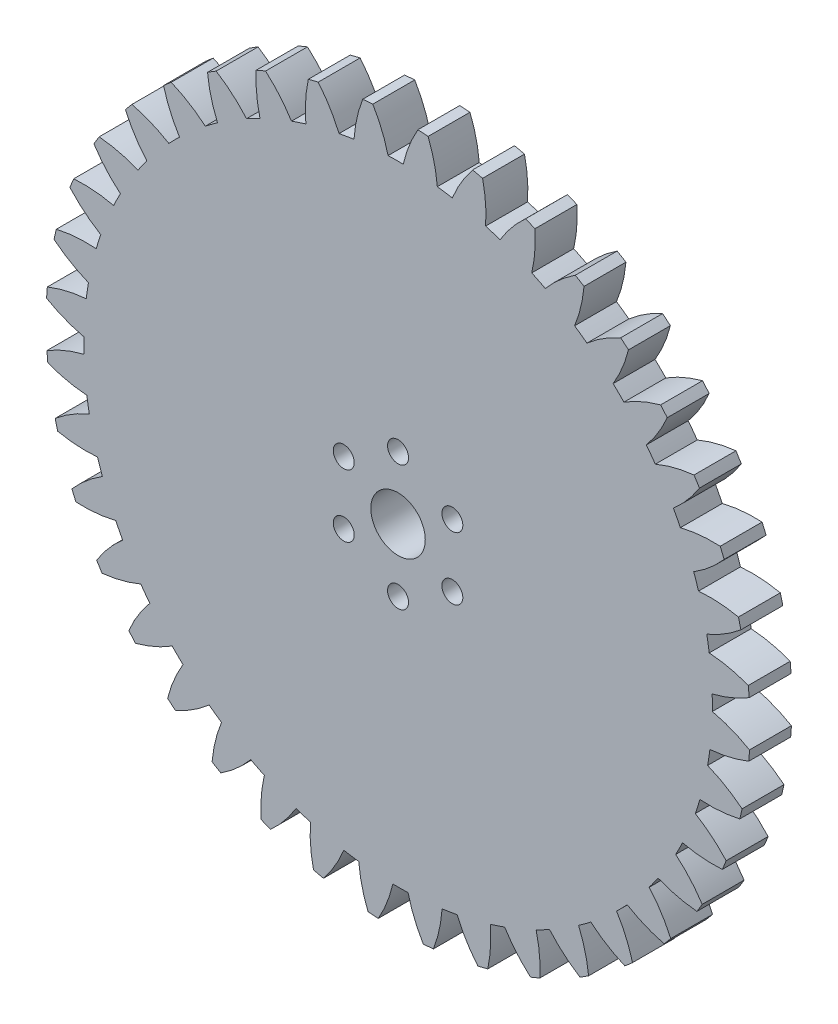
SolidWorks part; units mm, degrees
ref_plane "Front Plane" through (0, 0, 0) normal (0, 0, 1) x (1, 0, 0)
ref_plane "Top Plane" through (0, 0, 0) normal (0, 1, 0) x (1, 0, 0)
ref_plane "Right Plane" through (0, 0, 0) normal (1, 0, 0) x (0, 0, -1)
sketch "Sketch1" plane through (0, 0, 0) normal (0, 0, 1) x (1, 0, 0)
  circle A0 centre (0, 0) radius 9.5 construction
  circle A1 centre (0, 9.5) radius 1.5875
  circle A2 centre (8.2272, 4.75) radius 1.5875
  circle A3 centre (8.2272, -4.75) radius 1.5875
  circle A4 centre (0, -9.5) radius 1.5875
  circle A5 centre (-8.2272, -4.75) radius 1.5875
  circle A6 centre (-8.2272, 4.75) radius 1.5875
  circle A7 centre (0, 0) radius 4.125
  point P17 (0, 0)
  arc B0 (-53.2553, 3.0046) -> (-47.6173, 0.7826) centre (-43.069, 20.587) ccw
  arc B1 (-47.6173, 0.7826) -> (-47.5997, -1.5139) centre (0, 0) ccw
  arc B2 (-47.5997, -1.5139) -> (-53.2029, -3.8222) centre (-42.7477, -21.2461) ccw
  arc B3 (-53.2029, -3.8222) -> (-53.0697, -5.3634) centre (0, 0) ccw
  arc B4 (-53.0697, -5.3634) -> (-47.1535, -6.676) centre (-45.7593, 13.5961) ccw
  arc B5 (-47.1535, -6.676) -> (-46.7768, -8.9415) centre (0, 0) ccw
  arc B6 (-46.7768, -8.9415) -> (-51.9499, -12.0979) centre (-38.8978, -27.6718) ccw
  arc B7 (-51.9499, -12.0979) -> (-51.5773, -13.5993) centre (0, 0) ccw
  arc B8 (-51.5773, -13.5993) -> (-45.5286, -13.9703) centre (-47.3228, 6.2704) ccw
  arc B9 (-45.5286, -13.9703) -> (-44.8022, -16.1489) centre (0, 0) ccw
  arc B10 (-44.8022, -16.1489) -> (-49.4178, -20.0758) centre (-34.0901, -33.416) ccw
  arc B11 (-49.4178, -20.0758) -> (-48.8149, -21.5003) centre (0, 0) ccw
  arc B12 (-48.8149, -21.5003) -> (-42.7826, -20.9205) centre (-47.7211, -1.2098) ccw
  arc B13 (-42.7826, -20.9205) -> (-41.7243, -22.9587) centre (0, 0) ccw
  arc B14 (-41.7243, -22.9587) -> (-45.6688, -27.5592) centre (-28.4429, -38.3375) ccw
  arc B15 (-45.6688, -27.5592) -> (-44.8505, -28.8719) centre (0, 0) ccw
  arc B16 (-44.8505, -28.8719) -> (-38.9832, -27.3556) centre (-46.9443, -8.6601) ccw
  arc B17 (-38.9832, -27.3556) -> (-37.6191, -29.2031) centre (0, 0) ccw
  arc B18 (-37.6191, -29.2031) -> (-40.7954, -34.3641) centre (-22.0955, -42.3149) ccw
  arc B19 (-40.7954, -34.3641) -> (-39.7818, -35.5326) centre (0, 0) ccw
  arc B20 (-39.7818, -35.5326) -> (-34.2239, -33.1172) centre (-45.0116, -15.8972) ccw
  arc B21 (-34.2239, -33.1172) -> (-32.5876, -34.7285) centre (0, 0) ccw
  arc B22 (-32.5876, -34.7285) -> (-34.9174, -40.3228) centre (-15.2039, -45.2505) ccw
  arc B23 (-34.9174, -40.3228) -> (-33.7334, -41.3184) centre (0, 0) ccw
  arc B24 (-33.7334, -41.3184) -> (-28.6219, -38.0632) centre (-41.9706, -22.7428) ccw
  arc B25 (-28.6219, -38.0632) -> (-26.7536, -39.3988) centre (0, 0) ccw
  arc B26 (-26.7536, -39.3988) -> (-28.1796, -45.2887) centre (-7.938, -47.0718) ccw
  arc B27 (-28.1796, -45.2887) -> (-26.8545, -46.0868) centre (0, 0) ccw
  arc B28 (-26.8545, -46.0868) -> (-22.3151, -42.072) centre (-37.8961, -29.0284) ccw
  arc B29 (-22.3151, -42.072) -> (-20.2609, -43.0989) centre (0, 0) ccw
  arc B30 (-20.2609, -43.0989) -> (-20.748, -49.1394) centre (-0.4766, -47.734) ccw
  arc B31 (-20.748, -49.1394) -> (-19.3143, -49.7203) centre (0, 0) ccw
  arc B32 (-19.3143, -49.7203) -> (-15.4588, -45.0449) centre (-32.8885, -34.5993) ccw
  arc B33 (-15.4588, -45.0449) -> (-13.2693, -45.7378) centre (0, 0) ccw
  arc B34 (-13.2693, -45.7378) -> (-12.8054, -51.7801) centre (6.9965, -47.2209) ccw
  arc B35 (-12.8054, -51.7801) -> (-11.2986, -52.1296) centre (0, 0) ccw
  arc B36 (-11.2986, -52.1296) -> (-8.2219, -46.9086) centre (-27.071, -39.3182) ccw
  arc B37 (-8.2219, -46.9086) -> (-5.951, -47.2505) centre (0, 0) ccw
  arc B38 (-5.951, -47.2505) -> (-4.5476, -53.1458) centre (14.2973, -45.545) ccw
  arc B39 (-4.5476, -53.1458) -> (-3.0046, -53.2553) centre (0, 0) ccw
  arc B40 (-3.0046, -53.2553) -> (-0.7826, -47.6173) centre (-20.587, -43.069) ccw
  arc B41 (-0.7826, -47.6173) -> (1.5139, -47.5997) centre (0, 0) ccw
  arc B42 (1.5139, -47.5997) -> (3.8222, -53.2029) centre (21.2461, -42.7477) ccw
  arc B43 (3.8222, -53.2029) -> (5.3634, -53.0697) centre (0, 0) ccw
  arc B44 (5.3634, -53.0697) -> (6.676, -47.1535) centre (-13.5961, -45.7593) ccw
  arc B45 (6.676, -47.1535) -> (8.9415, -46.7768) centre (0, 0) ccw
  arc B46 (8.9415, -46.7768) -> (12.0979, -51.9499) centre (27.6718, -38.8978) ccw
  arc B47 (12.0979, -51.9499) -> (13.5993, -51.5773) centre (0, 0) ccw
  arc B48 (13.5993, -51.5773) -> (13.9703, -45.5286) centre (-6.2704, -47.3228) ccw
  arc B49 (13.9703, -45.5286) -> (16.1489, -44.8022) centre (0, 0) ccw
  arc B50 (16.1489, -44.8022) -> (20.0758, -49.4178) centre (33.416, -34.0901) ccw
  arc B51 (20.0758, -49.4178) -> (21.5003, -48.8149) centre (0, 0) ccw
  arc B52 (21.5003, -48.8149) -> (20.9205, -42.7826) centre (1.2098, -47.7211) ccw
  arc B53 (20.9205, -42.7826) -> (22.9587, -41.7243) centre (0, 0) ccw
  arc B54 (22.9587, -41.7243) -> (27.5592, -45.6688) centre (38.3375, -28.4429) ccw
  arc B55 (27.5592, -45.6688) -> (28.8719, -44.8505) centre (0, 0) ccw
  arc B56 (28.8719, -44.8505) -> (27.3556, -38.9832) centre (8.6601, -46.9443) ccw
  arc B57 (27.3556, -38.9832) -> (29.2031, -37.6191) centre (0, 0) ccw
  arc B58 (29.2031, -37.6191) -> (34.3641, -40.7954) centre (42.3149, -22.0955) ccw
  arc B59 (34.3641, -40.7954) -> (35.5326, -39.7818) centre (0, 0) ccw
  arc B60 (35.5326, -39.7818) -> (33.1172, -34.2239) centre (15.8972, -45.0116) ccw
  arc B61 (33.1172, -34.2239) -> (34.7285, -32.5876) centre (0, 0) ccw
  arc B62 (34.7285, -32.5876) -> (40.3228, -34.9174) centre (45.2505, -15.2039) ccw
  arc B63 (40.3228, -34.9174) -> (41.3184, -33.7334) centre (0, 0) ccw
  arc B64 (41.3184, -33.7334) -> (38.0632, -28.6219) centre (22.7428, -41.9706) ccw
  arc B65 (38.0632, -28.6219) -> (39.3988, -26.7536) centre (0, 0) ccw
  arc B66 (39.3988, -26.7536) -> (45.2887, -28.1796) centre (47.0718, -7.938) ccw
  arc B67 (45.2887, -28.1796) -> (46.0868, -26.8545) centre (0, 0) ccw
  arc B68 (46.0868, -26.8545) -> (42.072, -22.3151) centre (29.0284, -37.8961) ccw
  arc B69 (42.072, -22.3151) -> (43.0989, -20.2609) centre (0, 0) ccw
  arc B70 (43.0989, -20.2609) -> (49.1394, -20.748) centre (47.734, -0.4766) ccw
  arc B71 (49.1394, -20.748) -> (49.7203, -19.3143) centre (0, 0) ccw
  arc B72 (49.7203, -19.3143) -> (45.0449, -15.4588) centre (34.5993, -32.8885) ccw
  arc B73 (45.0449, -15.4588) -> (45.7378, -13.2693) centre (0, 0) ccw
  arc B74 (45.7378, -13.2693) -> (51.7801, -12.8054) centre (47.2209, 6.9965) ccw
  arc B75 (51.7801, -12.8054) -> (52.1296, -11.2986) centre (0, 0) ccw
  arc B76 (52.1296, -11.2986) -> (46.9086, -8.2219) centre (39.3182, -27.071) ccw
  arc B77 (46.9086, -8.2219) -> (47.2505, -5.951) centre (0, 0) ccw
  arc B78 (47.2505, -5.951) -> (53.1458, -4.5476) centre (45.545, 14.2973) ccw
  arc B79 (53.1458, -4.5476) -> (53.2553, -3.0046) centre (0, 0) ccw
  arc B80 (53.2553, -3.0046) -> (47.6173, -0.7826) centre (43.069, -20.587) ccw
  arc B81 (47.6173, -0.7826) -> (47.5997, 1.5139) centre (0, 0) ccw
  arc B82 (47.5997, 1.5139) -> (53.2029, 3.8222) centre (42.7477, 21.2461) ccw
  arc B83 (53.2029, 3.8222) -> (53.0697, 5.3634) centre (0, 0) ccw
  arc B84 (53.0697, 5.3634) -> (47.1535, 6.676) centre (45.7593, -13.5961) ccw
  arc B85 (47.1535, 6.676) -> (46.7768, 8.9415) centre (0, 0) ccw
  arc B86 (46.7768, 8.9415) -> (51.9499, 12.0979) centre (38.8978, 27.6718) ccw
  arc B87 (51.9499, 12.0979) -> (51.5773, 13.5993) centre (0, 0) ccw
  arc B88 (51.5773, 13.5993) -> (45.5286, 13.9703) centre (47.3228, -6.2704) ccw
  arc B89 (45.5286, 13.9703) -> (44.8022, 16.1489) centre (0, 0) ccw
  arc B90 (44.8022, 16.1489) -> (49.4178, 20.0758) centre (34.0901, 33.416) ccw
  arc B91 (49.4178, 20.0758) -> (48.8149, 21.5003) centre (0, 0) ccw
  arc B92 (48.8149, 21.5003) -> (42.7826, 20.9205) centre (47.7211, 1.2098) ccw
  arc B93 (42.7826, 20.9205) -> (41.7243, 22.9587) centre (0, 0) ccw
  arc B94 (41.7243, 22.9587) -> (45.6688, 27.5592) centre (28.4429, 38.3375) ccw
  arc B95 (45.6688, 27.5592) -> (44.8505, 28.8719) centre (0, 0) ccw
  arc B96 (44.8505, 28.8719) -> (38.9832, 27.3556) centre (46.9443, 8.6601) ccw
  arc B97 (38.9832, 27.3556) -> (37.6191, 29.2031) centre (0, 0) ccw
  arc B98 (37.6191, 29.2031) -> (40.7954, 34.3641) centre (22.0955, 42.3149) ccw
  arc B99 (40.7954, 34.3641) -> (39.7818, 35.5326) centre (0, 0) ccw
  arc B100 (39.7818, 35.5326) -> (34.2239, 33.1172) centre (45.0116, 15.8972) ccw
  arc B101 (34.2239, 33.1172) -> (32.5876, 34.7285) centre (0, 0) ccw
  arc B102 (32.5876, 34.7285) -> (34.9174, 40.3228) centre (15.2039, 45.2505) ccw
  arc B103 (34.9174, 40.3228) -> (33.7334, 41.3184) centre (0, 0) ccw
  arc B104 (33.7334, 41.3184) -> (28.6219, 38.0632) centre (41.9706, 22.7428) ccw
  arc B105 (28.6219, 38.0632) -> (26.7536, 39.3988) centre (0, 0) ccw
  arc B106 (26.7536, 39.3988) -> (28.1796, 45.2887) centre (7.938, 47.0718) ccw
  arc B107 (28.1796, 45.2887) -> (26.8545, 46.0868) centre (0, 0) ccw
  arc B108 (26.8545, 46.0868) -> (22.3151, 42.072) centre (37.8961, 29.0284) ccw
  arc B109 (22.3151, 42.072) -> (20.2609, 43.0989) centre (0, 0) ccw
  arc B110 (20.2609, 43.0989) -> (20.748, 49.1394) centre (0.4766, 47.734) ccw
  arc B111 (20.748, 49.1394) -> (19.3143, 49.7203) centre (0, 0) ccw
  arc B112 (19.3143, 49.7203) -> (15.4588, 45.0449) centre (32.8885, 34.5993) ccw
  arc B113 (15.4588, 45.0449) -> (13.2693, 45.7378) centre (0, 0) ccw
  arc B114 (13.2693, 45.7378) -> (12.8054, 51.7801) centre (-6.9965, 47.2209) ccw
  arc B115 (12.8054, 51.7801) -> (11.2986, 52.1296) centre (0, 0) ccw
  arc B116 (11.2986, 52.1296) -> (8.2219, 46.9086) centre (27.071, 39.3182) ccw
  arc B117 (8.2219, 46.9086) -> (5.951, 47.2505) centre (0, 0) ccw
  arc B118 (5.951, 47.2505) -> (4.5476, 53.1458) centre (-14.2973, 45.545) ccw
  arc B119 (4.5476, 53.1458) -> (3.0046, 53.2553) centre (0, 0) ccw
  arc B120 (3.0046, 53.2553) -> (0.7826, 47.6173) centre (20.587, 43.069) ccw
  arc B121 (0.7826, 47.6173) -> (-1.5139, 47.5997) centre (0, 0) ccw
  arc B122 (-1.5139, 47.5997) -> (-3.8222, 53.2029) centre (-21.2461, 42.7477) ccw
  arc B123 (-3.8222, 53.2029) -> (-5.3634, 53.0697) centre (0, 0) ccw
  arc B124 (-5.3634, 53.0697) -> (-6.676, 47.1535) centre (13.5961, 45.7593) ccw
  arc B125 (-6.676, 47.1535) -> (-8.9415, 46.7768) centre (0, 0) ccw
  arc B126 (-8.9415, 46.7768) -> (-12.0979, 51.9499) centre (-27.6718, 38.8978) ccw
  arc B127 (-12.0979, 51.9499) -> (-13.5993, 51.5773) centre (0, 0) ccw
  arc B128 (-13.5993, 51.5773) -> (-13.9703, 45.5286) centre (6.2704, 47.3228) ccw
  arc B129 (-13.9703, 45.5286) -> (-16.1489, 44.8022) centre (0, 0) ccw
  arc B130 (-16.1489, 44.8022) -> (-20.0758, 49.4178) centre (-33.416, 34.0901) ccw
  arc B131 (-20.0758, 49.4178) -> (-21.5003, 48.8149) centre (0, 0) ccw
  arc B132 (-21.5003, 48.8149) -> (-20.9205, 42.7826) centre (-1.2098, 47.7211) ccw
  arc B133 (-20.9205, 42.7826) -> (-22.9587, 41.7243) centre (0, 0) ccw
  arc B134 (-22.9587, 41.7243) -> (-27.5592, 45.6688) centre (-38.3375, 28.4429) ccw
  arc B135 (-27.5592, 45.6688) -> (-28.8719, 44.8505) centre (0, 0) ccw
  arc B136 (-28.8719, 44.8505) -> (-27.3556, 38.9832) centre (-8.6601, 46.9443) ccw
  arc B137 (-27.3556, 38.9832) -> (-29.2031, 37.6191) centre (0, 0) ccw
  arc B138 (-29.2031, 37.6191) -> (-34.3641, 40.7954) centre (-42.3149, 22.0955) ccw
  arc B139 (-34.3641, 40.7954) -> (-35.5326, 39.7818) centre (0, 0) ccw
  arc B140 (-35.5326, 39.7818) -> (-33.1172, 34.2239) centre (-15.8972, 45.0116) ccw
  arc B141 (-33.1172, 34.2239) -> (-34.7285, 32.5876) centre (0, 0) ccw
  arc B142 (-34.7285, 32.5876) -> (-40.3228, 34.9174) centre (-45.2505, 15.2039) ccw
  arc B143 (-40.3228, 34.9174) -> (-41.3184, 33.7334) centre (0, 0) ccw
  arc B144 (-41.3184, 33.7334) -> (-38.0632, 28.6219) centre (-22.7428, 41.9706) ccw
  arc B145 (-38.0632, 28.6219) -> (-39.3988, 26.7536) centre (0, 0) ccw
  arc B146 (-39.3988, 26.7536) -> (-45.2887, 28.1796) centre (-47.0718, 7.938) ccw
  arc B147 (-45.2887, 28.1796) -> (-46.0868, 26.8545) centre (0, 0) ccw
  arc B148 (-46.0868, 26.8545) -> (-42.072, 22.3151) centre (-29.0284, 37.8961) ccw
  arc B149 (-42.072, 22.3151) -> (-43.0989, 20.2609) centre (0, 0) ccw
  arc B150 (-43.0989, 20.2609) -> (-49.1394, 20.748) centre (-47.734, 0.4766) ccw
  arc B151 (-49.1394, 20.748) -> (-49.7203, 19.3143) centre (0, 0) ccw
  arc B152 (-49.7203, 19.3143) -> (-45.0449, 15.4588) centre (-34.5993, 32.8885) ccw
  arc B153 (-45.0449, 15.4588) -> (-45.7378, 13.2693) centre (0, 0) ccw
  arc B154 (-45.7378, 13.2693) -> (-51.7801, 12.8054) centre (-47.2209, -6.9965) ccw
  arc B155 (-51.7801, 12.8054) -> (-52.1296, 11.2986) centre (0, 0) ccw
  arc B156 (-52.1296, 11.2986) -> (-46.9086, 8.2219) centre (-39.3182, 27.071) ccw
  arc B157 (-46.9086, 8.2219) -> (-47.2505, 5.951) centre (0, 0) ccw
  arc B158 (-47.2505, 5.951) -> (-53.1458, 4.5476) centre (-45.545, -14.2973) ccw
  arc B159 (-53.1458, 4.5476) -> (-53.2553, 3.0046) centre (0, 0) ccw
  dimension "D1" = 19
  dimension "D2" = 3.175
  dimension "D4" = 8.25
  dimension "D3" = 6
sketch_block_instance "Center_Gear-1"
sketch_block "Center_Gear"
extrude "Boss-Extrude1" add sketch "Sketch1" along normal blind 6.35
sketch "Sketch2" plane through (0, 0, 0) normal (0, 0, -1) x (-1, 0, 0)
  circle B0 centre (8.2272, -4.75) radius 1.5875
  circle B1 centre (8.2272, 4.75) radius 1.5875
  circle B2 centre (0, 9.5) radius 1.5875
  circle B3 centre (-8.2272, 4.75) radius 1.5875
  circle B4 centre (-8.2272, -4.75) radius 1.5875
  circle B5 centre (0, 0) radius 4.125
  circle B6 centre (0, -9.5) radius 1.5875
sketch_block_instance "Block1-1"
sketch_block "Block1"
